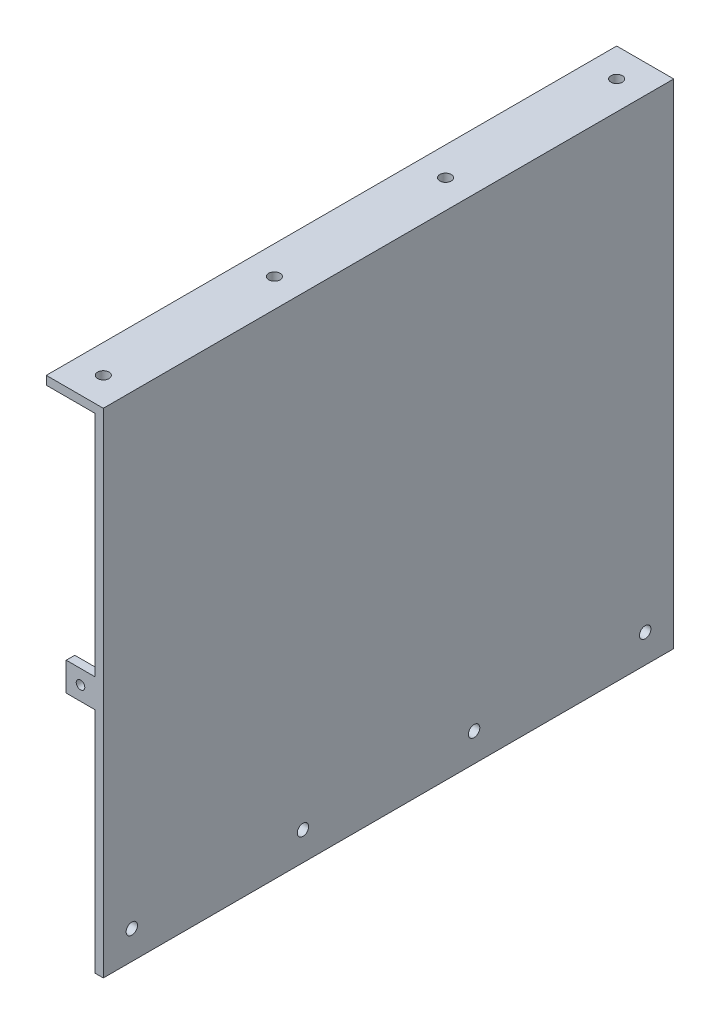
SolidWorks part; units mm, degrees
ref_plane "Front Plane" through (0, 0, 0) normal (0, 0, 1) x (1, 0, 0)
ref_plane "Top Plane" through (0, 0, 0) normal (0, 1, 0) x (1, 0, 0)
ref_plane "Right Plane" through (0, 0, 0) normal (1, 0, 0) x (0, 0, -1)
sketch "Sketch1" plane through (0, 0, 0) normal (0, 1, 0) x (1, 0, 0)
  line L1 (-10, -100) -> (10, -100)
  line L2 (-10, -100) -> (-10, 100)
  line L3 (-10, 100) -> (10, 100)
  line L4 (10, -100) -> (10, 100)
  line L5 (-10, -100) -> (10, 100) construction
  line L6 (-10, 100) -> (10, -100) construction
  point P0 (0, 0)
  dimension "D1" = 20
  dimension "D2" = 200
extrude "Boss-Extrude1" add sketch "Sketch1" along normal blind 3
sketch "Sketch2" plane through (0, 0, 0) normal (0, -1, 0) x (1, 0, 0)
  line L0 (10, -100) -> (-10, -100) construction
  line L1 (10, 100) -> (7, 100)
  line L2 (10, 100) -> (10, -100)
  line L3 (10, -100) -> (7, -100)
  line L4 (7, 100) -> (7, -100)
  dimension "D1" = 3
extrude "Boss-Extrude2" add sketch "Sketch2" along normal blind 170
sketch "Sketch3" plane through (0, 3, 0) normal (0, 1, 0) x (1, 0, 0)
  line L0 (-10, -100) -> (10, -100) construction
  line L1 (-10, 100) -> (-10, -100) construction
  circle A0 centre (0, -90) radius 2
  dimension "D1" = 4
  dimension "D2" = 10
  dimension "D3" = 10
extrude "Cut-Extrude1" cut sketch "Sketch3" against normal up to next
pattern_linear "LPattern1" count 4 spacing 60 along (0, 0, -1) of "Cut-Extrude1"
sketch "Sketch4" plane through (10, 0, 0) normal (1, 0, 0) x (0, 0, -1)
  line L0 (100, -170) -> (-100, -170) construction
  line L1 (100, 3) -> (100, -170) construction
  circle A0 centre (90, -160) radius 2
  dimension "D1" = 4
  dimension "D2" = 10
  dimension "D3" = 10
extrude "Cut-Extrude2" cut sketch "Sketch4" against normal up to next
pattern_linear "LPattern2" count 4 spacing 60 along (0, 0, 1) of "Cut-Extrude2"
sketch "Sketch5" plane through (7, 0, 0) normal (-1, 0, 0) x (0, 0, 1)
  line L0 (-100, -170) -> (-100, 0) construction
  line L1 (-100, -80) -> (-97, -80)
  line L2 (-100, -80) -> (-100, -90)
  line L3 (-100, -90) -> (-97, -90)
  line L4 (-97, -80) -> (-97, -90)
  dimension "D1" = 3
  dimension "D2" = 10
  dimension "D3" = 80
extrude "Boss-Extrude3" add sketch "Sketch5" along normal blind 10
sketch "Sketch6" plane through (0, 0, -100) normal (0, 0, -1) x (-1, 0, 0)
  line L0 (3, -80) -> (-7, -80) construction
  line L1 (3, -80) -> (3, -90) construction
  circle A0 centre (-2, -85) radius 1.5
  dimension "D1" = 3
  dimension "D2" = 5
  dimension "D3" = 5
extrude "Cut-Extrude3" cut sketch "Sketch6" against normal up to next
mirror "Mirror1" about plane through (0, 0, 0) normal (0, 0, 1) of "Cut-Extrude3", "Boss-Extrude3"
